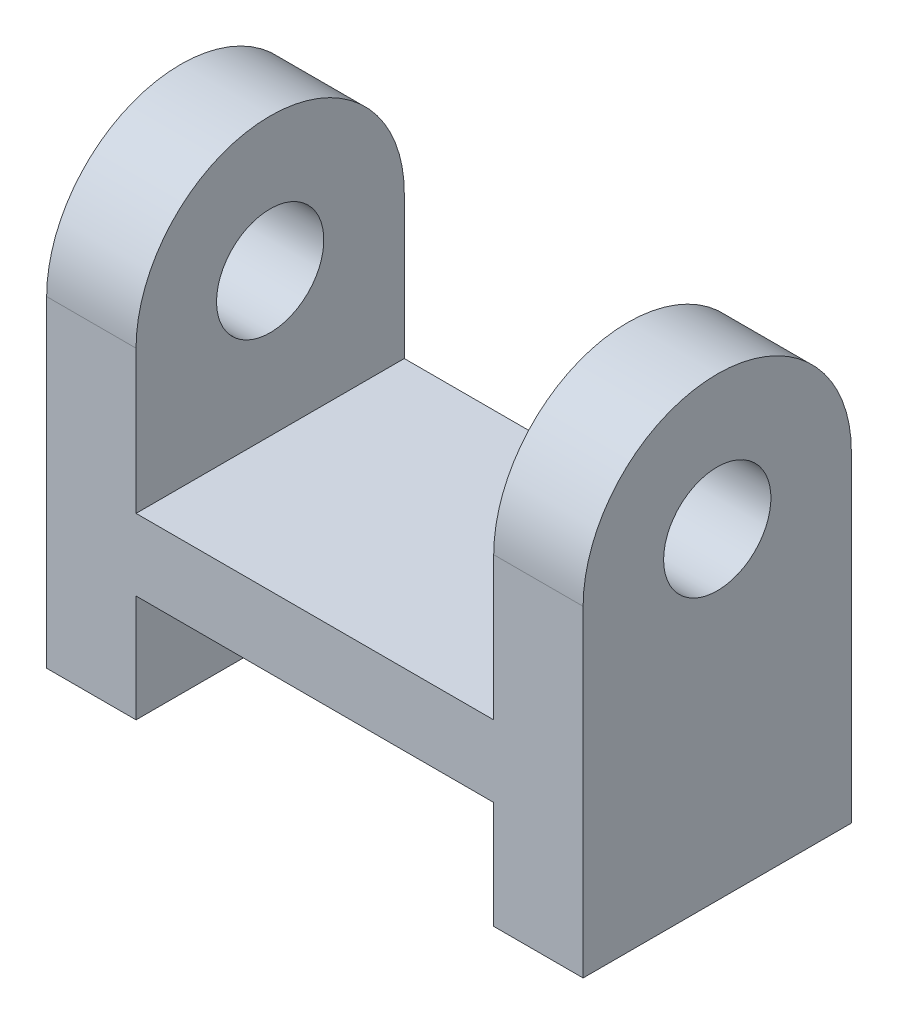
SolidWorks part; units mm, degrees
ref_plane "前视基准面" through (0, 0, 0) normal (0, 0, 1) x (1, 0, 0)
ref_plane "上视基准面" through (0, 0, 0) normal (0, 1, 0) x (1, 0, 0)
ref_plane "右视基准面" through (0, 0, 0) normal (1, 0, 0) x (0, 0, -1)
sketch "草图1" plane through (0, 0, 0) normal (0, 0, 1) x (1, 0, 0)
  line L0 (0, 0) -> (0, 5.9499) construction
  line L1 (10, 6) -> (-10, 6)
  line L2 (-10, 6) -> (-10, 0)
  line L3 (10, 6) -> (10, 0)
  line L4 (-10, 0) -> (-15, 0)
  line L5 (10, 0) -> (15, 0)
  line L6 (-15, 0) -> (-15, 10)
  line L7 (15, 0) -> (15, 10)
  line L8 (-15, 10) -> (15, 10)
  point P6 (0, 6)
  point P12 (0, 10)
  point P13 (8.5028, 0)
  dimension "D1" = 20
  dimension "D2" = 6
  dimension "D3" = 30
  dimension "D4" = 10
extrude "凸台-拉伸1" add sketch "草图1" along normal blind 15
sketch "草图2" plane through (-15, 0, 0) normal (-1, 0, 0) x (0, 0, 1)
  line L0 (0, 10) -> (0, 18)
  line L1 (15, 18) -> (15, 10)
  line L2 (0, 10) -> (15, 10)
  arc A0 (0, 18) -> (15, 18) centre (7.5, 18) cw
  dimension "D1" = 8
extrude "凸台-拉伸2" add sketch "草图2" against normal blind 5
ref_plane "基准面1" through (0, 0, 0) normal (1, 0, 0) x (0, 0, -1)
sketch "草图4" plane through (-15, 0, 0) normal (-1, 0, 0) x (0, 0, 1)
  circle A0 centre (7.5, 18) radius 3
  dimension "D1" = 6
extrude "切除-拉伸1" cut sketch "草图4" against normal blind 5
mirror "镜向2" about plane through (0, 0, 0) normal (1, 0, 0) of "凸台-拉伸2", "切除-拉伸1"
